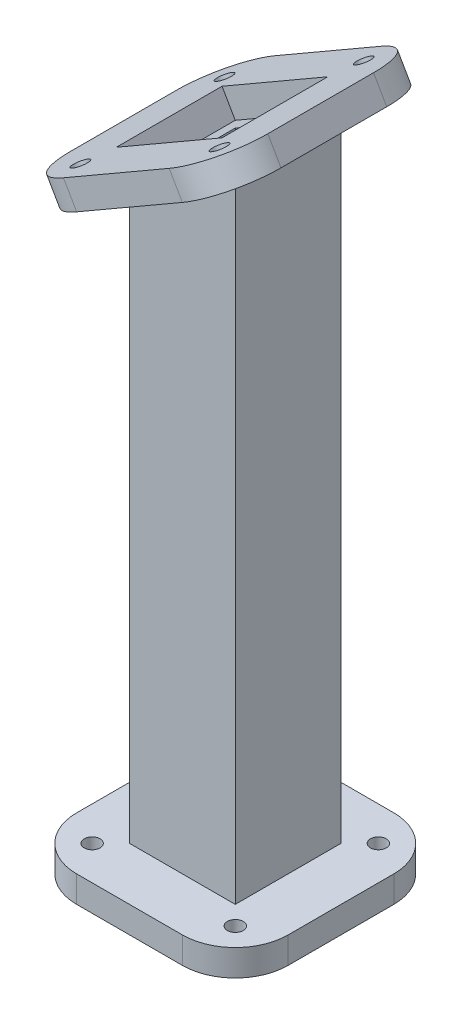
SolidWorks part; units mm, degrees
ref_plane "Plan de face" through (0, 0, 0) normal (0, 0, 1) x (1, 0, 0)
ref_plane "Plan de dessus" through (0, 0, 0) normal (0, 1, 0) x (1, 0, 0)
ref_plane "Plan de droite" through (0, 0, 0) normal (1, 0, 0) x (0, 0, -1)
sketch "Esquisse1" plane through (0, 0, 0) normal (0, 0, 1) x (1, 0, 0)
  line L0 (10, 60) -> (-10, 48.453)
  line L1 (-10, 60) -> (10, 60) construction
  line L2 (-10, 60) -> (-10, -60) construction
  line L3 (-10, -60) -> (10, -60)
  line L4 (10, 60) -> (10, -60)
  line L5 (-10, 60) -> (10, -60) construction
  line L6 (-10, -60) -> (10, 60) construction
  line L7 (-10, 48.453) -> (-10, -60)
  point P0 (0, 0)
  dimension "D1" = 20
  dimension "D2" = 120
  dimension "D3" = 30
extrude "Boss.-Extru.1" add sketch "Esquisse1" along normal blind 20
shell "Coque1" thickness 3
sketch "Esquisse2" plane through (0, -60, 0) normal (0, -1, 0) x (1, 0, 0)
  line L0 (-20, 20) -> (-20, 0)
  line L1 (-10, -10) -> (10, -10)
  line L2 (20, 0) -> (20, 20)
  line L3 (10, 30) -> (-10, 30)
  line L4 (-10, 0) -> (10, 0)
  line L5 (10, 0) -> (10, 20)
  line L6 (10, 20) -> (-10, 20)
  line L7 (-10, 20) -> (-10, 0)
  line L8 (-10, 0) -> (10, 0)
  line L9 (10, 0) -> (10, 20)
  line L10 (10, 20) -> (-10, 20)
  line L11 (-10, 20) -> (-10, 0)
  line L12 (-20, -10) -> (20, -10) construction
  line L13 (20, -10) -> (20, 30) construction
  line L14 (-20, 30) -> (-20, -10) construction
  line L15 (20, 30) -> (-20, 30) construction
  line L16 (-17.0711, 27.0711) -> (-10, 20) construction
  line L17 (-7, 17) -> (7, 3) construction
  line L18 (-7, 3) -> (7, 17) construction
  arc A0 (10, -10) -> (20, 0) centre (10, 0) ccw
  arc A1 (-20, 0) -> (-10, -10) centre (-10, 0) ccw
  arc A2 (20, 20) -> (10, 30) centre (10, 20) ccw
  arc A3 (-20, 20) -> (-10, 30) centre (-10, 20) cw
  circle A4 centre (-13.5355, 23.5355) radius 1.5
  circle A5 centre (0, 10) radius 19.1421 construction
  circle A6 centre (13.5355, 23.5355) radius 1.5
  circle A7 centre (13.5355, -3.5355) radius 1.5
  circle A8 centre (-13.5355, -3.5355) radius 1.5
  point P42 (0, 10)
  dimension "D3" = 10
  dimension "D4" = 3
  dimension "D5" = 4
  dimension "D1" = 0
  dimension "D2" = 10
extrude "Boss.-Extru.2" add sketch "Esquisse2" along normal blind 5 separate body
sketch "Esquisse3" plane through (-23.4808, 40.6699, 0) normal (-0.5, 0.866, 0) x (0.866, 0.5, 0)
  line L1 (38.6603, 10) -> (15.5662, 10)
  line L2 (5.5662, 0) -> (5.5662, -20)
  line L3 (15.5662, -30) -> (38.6603, -30)
  line L4 (38.6603, 0) -> (15.5662, 0)
  line L5 (15.5662, 0) -> (15.5662, -20)
  line L6 (15.5662, -20) -> (38.6603, -20)
  line L7 (38.6603, -20) -> (38.6603, 0)
  line L8 (38.6603, 0) -> (15.5662, 0)
  line L9 (15.5662, 0) -> (15.5662, -20)
  line L10 (15.5662, -20) -> (38.6603, -20)
  line L11 (38.6603, -20) -> (38.6603, 0)
  line L12 (48.6603, -20) -> (48.6603, 0)
  line L13 (48.6603, 10) -> (5.5662, 10) construction
  line L14 (48.6603, -30) -> (48.6603, 10) construction
  line L15 (5.5662, -30) -> (48.6603, -30) construction
  line L16 (5.5662, 10) -> (5.5662, -30) construction
  line L17 (15.5662, 0) -> (8.4952, 7.0711) construction
  line L18 (15.5662, 0) -> (38.6603, -20) construction
  line L19 (15.5662, -20) -> (38.6603, 0) construction
  arc A0 (38.6603, 10) -> (48.6603, 0) centre (38.6603, 0) cw
  arc A1 (38.6603, -30) -> (48.6603, -20) centre (38.6603, -20) ccw
  arc A2 (5.5662, -20) -> (15.5662, -30) centre (15.5662, -20) ccw
  arc A3 (15.5662, 10) -> (5.5662, 0) centre (15.5662, 0) ccw
  circle A4 centre (12.0307, 3.5355) radius 1.5
  circle A5 centre (27.1132, -10) radius 20.2656 construction
  circle A6 centre (40.6488, 5.0825) radius 1.5
  circle A7 centre (42.1958, -23.5355) radius 1.5
  circle A8 centre (13.5777, -25.0825) radius 1.5
  point P25 (0, 0)
  point P26 (0, 0)
  point P34 (27.1132, -10)
  dimension "D3" = 10
  dimension "D4" = 3
  dimension "D1" = 0
  dimension "D2" = 10
  dimension "D5" = 4
extrude "Boss.-Extru.3" add sketch "Esquisse3" along normal blind 5 separate body
